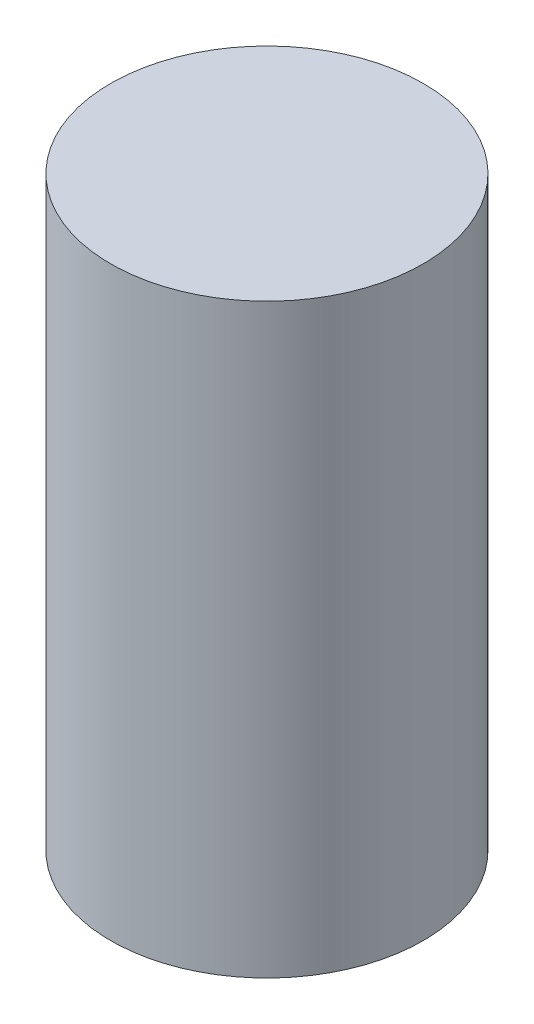
SolidWorks part; units mm, degrees
material "Вода"
ref_plane "Спереди" through (0, 0, 0) normal (0, 0, 1) x (1, 0, 0)
ref_plane "Сверху" through (0, 0, 0) normal (0, 1, 0) x (1, 0, 0)
ref_plane "Справа" through (0, 0, 0) normal (1, 0, 0) x (0, 0, -1)
sketch "Эскиз1" plane through (0, 0, 0) normal (0, 1, 0) x (1, 0, 0)
  circle A0 centre (0, 0) radius 48
  dimension "D1" = 96
extrude "Бобышка-Вытянуть1" add sketch "Эскиз1" along normal blind 180
